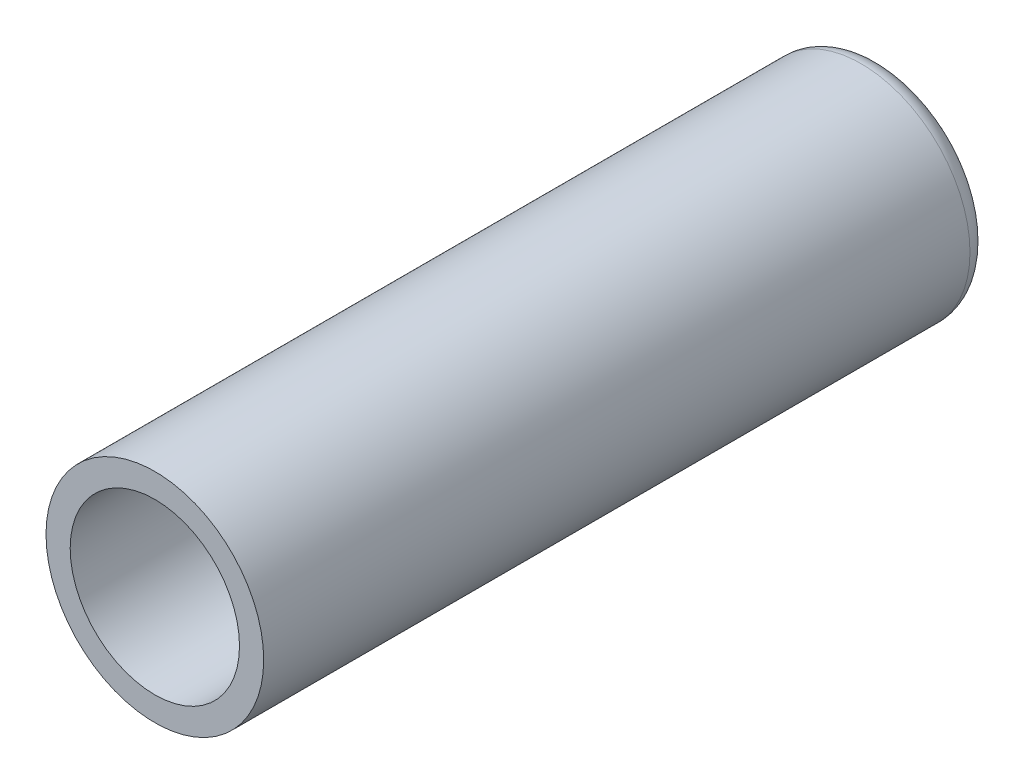
SolidWorks part; units mm, degrees
ref_plane "Front Plane" through (0, 0, 0) normal (0, 0, 1) x (1, 0, 0)
ref_plane "Top Plane" through (0, 0, 0) normal (0, 1, 0) x (1, 0, 0)
ref_plane "Right Plane" through (0, 0, 0) normal (1, 0, 0) x (0, 0, -1)
sketch "Sketch1" plane through (0, 0, 0) normal (0, 0, 1) x (1, 0, 0)
  circle A0 centre (0, 0) radius 14.2875
  dimension "D1" = 28.575
extrude "Boss-Extrude1" add sketch "Sketch1" along normal blind 95.25
sketch "Sketch2" plane through (0, 0, 95.25) normal (0, 0, 1) x (1, 0, 0)
  circle A0 centre (0, 0) radius 11.1125
  dimension "D1" = 22.225
extrude "Cut-Extrude1" cut sketch "Sketch2" against normal offset from surface (92.075 mm away) 3.175 up to face at (14.2875, 0, 0)
fillet "Fillet1" radius 2.54 1 edges at (14.2875, 0, 0)
